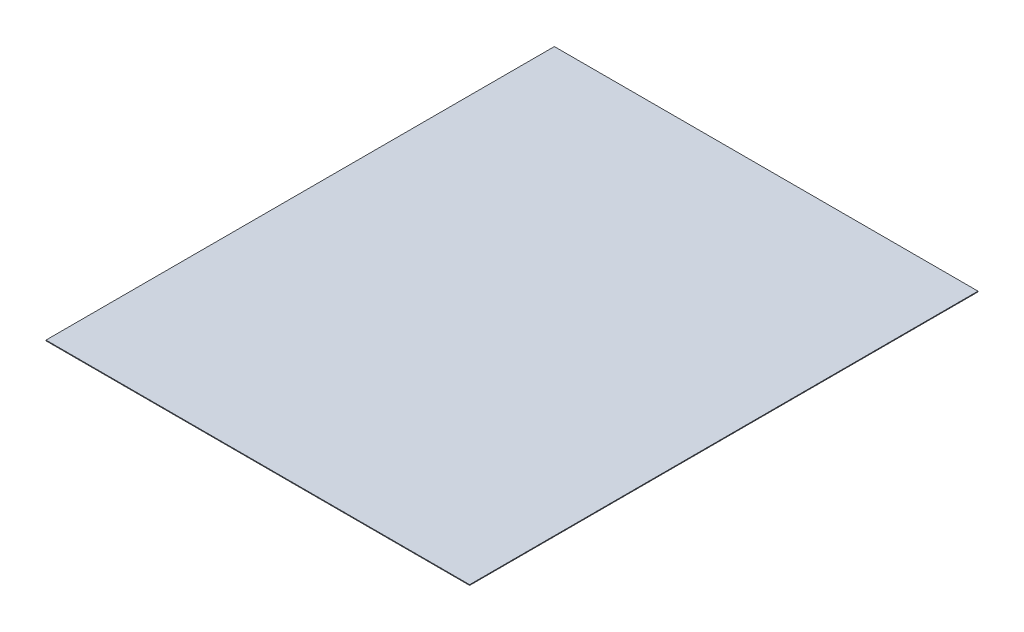
SolidWorks part; units mm, degrees
ref_plane "Front Plane" through (0, 0, 0) normal (0, 0, 1) x (1, 0, 0)
ref_plane "Top Plane" through (0, 0, 0) normal (0, 1, 0) x (1, 0, 0)
ref_plane "Right Plane" through (0, 0, 0) normal (1, 0, 0) x (0, 0, -1)
sketch "Esquisse1" plane through (0, 0, 0) normal (0, 1, 0) x (1, 0, 0)
  line L1 (-3000, 3600) -> (3000, 3600)
  line L2 (-3000, 3600) -> (-3000, -3600)
  line L3 (-3000, -3600) -> (3000, -3600)
  line L4 (3000, 3600) -> (3000, -3600)
  line L5 (-3000, 3600) -> (3000, -3600) construction
  line L6 (-3000, -3600) -> (3000, 3600) construction
  point P0 (0, 0)
extrude "Boss.-Extru.1" add sketch "Esquisse1" along normal blind 10
